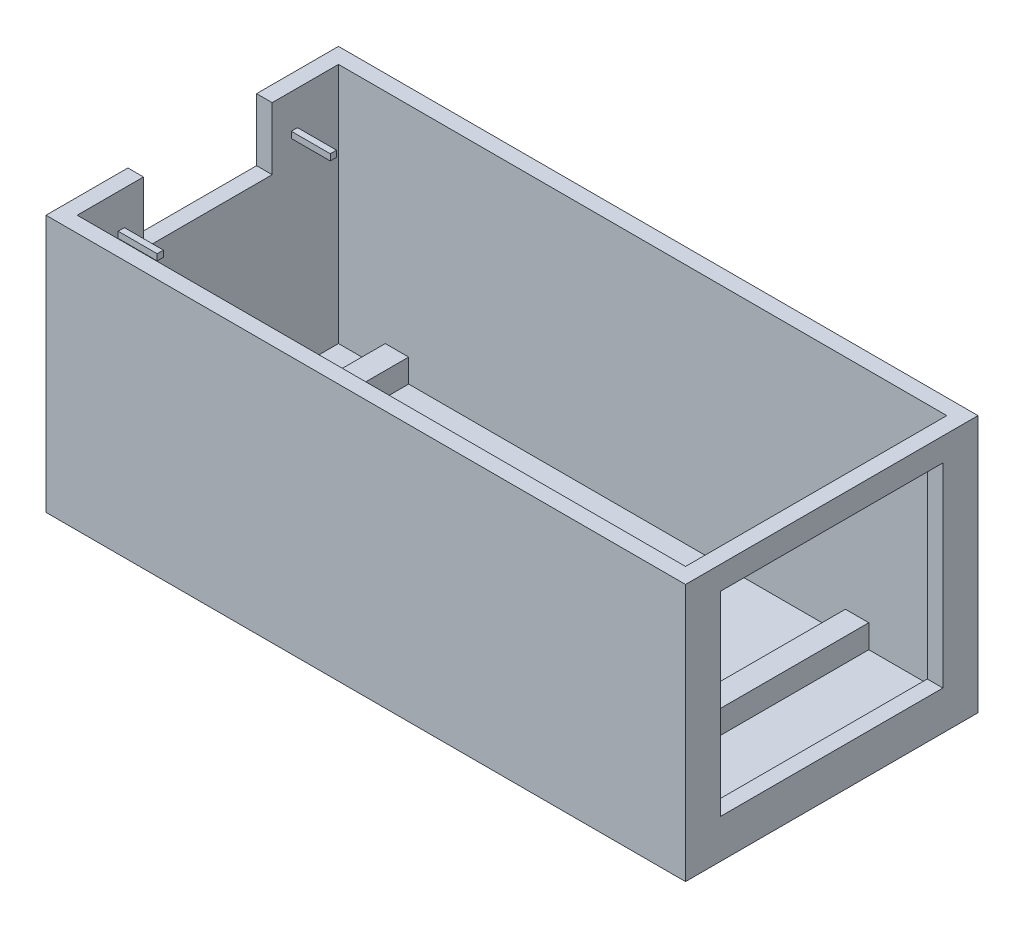
SolidWorks part; units mm, degrees
ref_plane "Front Plane" through (0, 0, 0) normal (0, 0, 1) x (1, 0, 0)
ref_plane "Top Plane" through (0, 0, 0) normal (0, 1, 0) x (1, 0, 0)
ref_plane "Right Plane" through (0, 0, 0) normal (1, 0, 0) x (0, 0, -1)
sketch "Sketch1" plane through (0, 0, 0) normal (0, 1, 0) x (1, 0, 0)
  line L1 (0, 0) -> (82, 0)
  line L2 (0, 0) -> (0, 37.5)
  line L3 (0, 37.5) -> (82, 37.5)
  line L4 (82, 0) -> (82, 37.5)
  dimension "D1" = 82
  dimension "D2" = 37.5
extrude "Boss-Extrude2" add sketch "Sketch1" along normal blind 2 contours L2 L3 L4 L1
sketch "Sketch2" plane through (0, 2, 0) normal (0, 1, 0) x (1, 0, 0)
  line L0 (0, 37.5) -> (82, 37.5) construction
  line L1 (8, 37.5) -> (11, 37.5)
  line L2 (8, 37.5) -> (8, 0)
  line L3 (8, 0) -> (11, 0)
  line L4 (11, 37.5) -> (11, 0)
  line L5 (0, 0) -> (82, 0) construction
  line L6 (0, 0) -> (0, 37.5) construction
  line L7 (67, 37.5) -> (70, 37.5)
  line L8 (67, 37.5) -> (67, 0)
  line L9 (67, 0) -> (70, 0)
  line L10 (70, 37.5) -> (70, 0)
  line L11 (82, 0) -> (82, 37.5) construction
  dimension "D1" = 3
  dimension "D2" = 8
  dimension "D3" = 12
  dimension "D4" = 3
extrude "Boss-Extrude4" add sketch "Sketch2" along normal blind 3
sketch "Sketch4" plane through (0, 2, 0) normal (0, 1, 0) x (1, 0, 0)
  line L0 (11, 37.5) -> (8, 37.5) construction
  line L1 (11, 37.5) -> (67, 37.5) construction
  line L2 (70, 37.5) -> (67, 37.5) construction
  line L3 (70, 37.5) -> (82, 37.5) construction
  line L4 (82, 0) -> (82, 37.5) construction
  line L5 (70, 0) -> (82, 0) construction
  line L6 (67, 0) -> (70, 0) construction
  line L7 (11, 0) -> (67, 0) construction
  line L8 (8, 0) -> (11, 0) construction
  line L9 (0, 0) -> (8, 0) construction
  line L10 (0, 0) -> (0, 37.5) construction
  line L11 (0, 37.5) -> (8, 37.5) construction
  line L12 (11, 37.5) -> (8, 37.5)
  line L13 (11, 37.5) -> (67, 37.5)
  line L14 (70, 37.5) -> (67, 37.5)
  line L15 (70, 37.5) -> (82, 37.5)
  line L16 (82, 0) -> (82, 37.5)
  line L17 (70, 0) -> (82, 0)
  line L18 (67, 0) -> (70, 0)
  line L19 (11, 0) -> (67, 0)
  line L20 (8, 0) -> (11, 0)
  line L21 (0, 0) -> (8, 0)
  line L22 (0, 0) -> (0, 37.5)
  line L23 (0, 37.5) -> (8, 37.5)
  line L24 (2, 2) -> (2, 35.5)
  line L25 (2, 35.5) -> (8, 35.5)
  line L26 (11, 35.5) -> (8, 35.5)
  line L27 (11, 35.5) -> (67, 35.5)
  line L28 (70, 35.5) -> (67, 35.5)
  line L29 (70, 35.5) -> (80, 35.5)
  line L30 (80, 2) -> (80, 35.5)
  line L31 (70, 2) -> (80, 2)
  line L32 (67, 2) -> (70, 2)
  line L33 (11, 2) -> (67, 2)
  line L34 (8, 2) -> (11, 2)
  line L35 (2, 2) -> (8, 2)
  dimension "D1" = 2
extrude "Boss-Extrude5" add sketch "Sketch4" along normal blind 31
sketch "Sketch6" plane through (0, 0, 0) normal (-1, 0, 0) x (0, 0, 1)
  line L0 (-37.5, 33) -> (0, 33) construction
  line L1 (-27, 33) -> (-10.5, 33)
  line L2 (-27, 33) -> (-27, 25)
  line L3 (-27, 25) -> (-10.5, 25)
  line L4 (-10.5, 33) -> (-10.5, 25)
  line L5 (-18.75, 0) -> (-18.75, 33.7611) construction
  line L6 (0, 0) -> (-37.5, 0) construction
  dimension "D1" = 16.5
  dimension "D2" = 8
extrude "Cut-Extrude1" cut sketch "Sketch6" against normal blind 2
sketch "Sketch7" plane through (82, 0, 0) normal (1, 0, 0) x (0, 0, -1)
  line L0 (0, 0) -> (37.5, 0) construction
  line L1 (4.5, 30) -> (33, 30)
  line L2 (4.5, 30) -> (4.5, 5)
  line L3 (4.5, 5) -> (33, 5)
  line L4 (33, 30) -> (33, 5)
  line L5 (18.75, 0) -> (18.75, 34.1605) construction
  dimension "D1" = 25
  dimension "D2" = 28.5
  dimension "D3" = 5
extrude "Cut-Extrude2" cut sketch "Sketch7" against normal blind 2
sketch "Sketch8" plane through (2, 0, 0) normal (1, 0, 0) x (0, 0, -1)
  line L0 (10.5, 33) -> (2, 33) construction
  line L1 (7.25, 28.6) -> (8.05, 28.6)
  line L2 (7.25, 28.6) -> (7.25, 27.8)
  line L3 (7.25, 27.8) -> (8.05, 27.8)
  line L4 (8.05, 28.6) -> (8.05, 27.8)
  line L5 (10.5, 25) -> (10.5, 33) construction
  line L6 (18.75, 25) -> (18.75, 37.7153) construction
  line L7 (27, 25) -> (10.5, 25) construction
  line L8 (30.25, 28.6) -> (30.25, 27.8)
  line L9 (30.25, 28.6) -> (29.45, 28.6)
  line L10 (29.45, 28.6) -> (29.45, 27.8)
  line L11 (30.25, 27.8) -> (29.45, 27.8)
  point P8 (7.25, 28.2)
  point P9 (8.05, 28.2)
  point P14 (7.65, 27.8)
  point P19 (29.85, 27.8)
  dimension "D1" = 4.4
  dimension "D2" = 2.45
  dimension "D3" = 0.8
  dimension "D4" = 0.8
extrude "Boss-Extrude6" add sketch "Sketch8" along normal blind 5
sketch "Sketch9" plane through (0, 0, -37.5) normal (0, 0, -1) x (-1, 0, 0)
  line L0 (-82, 33) -> (-82, 0) construction
  line L1 (-73, 27) -> (-38, 27)
  line L2 (-73, 27) -> (-73, 25)
  line L3 (-73, 25) -> (-38, 25)
  line L4 (-38, 27) -> (-38, 25)
  line L5 (-73, 6) -> (-38, 6)
  line L6 (-73, 6) -> (-73, 4)
  line L7 (-73, 4) -> (-38, 4)
  line L8 (-38, 6) -> (-38, 4)
  line L10 (-82, 33) -> (0, 33) construction
  point P8 (-38, 5)
  dimension "D1" = 2
  dimension "D2" = 2
  dimension "D3" = 35
  dimension "D4" = 35
  dimension "D5" = 9
  dimension "D6" = 9
  dimension "D7" = 19
  dimension "D8" = 6
extrude "Boss-Extrude7" add sketch "Sketch9" along normal blind 2.4
